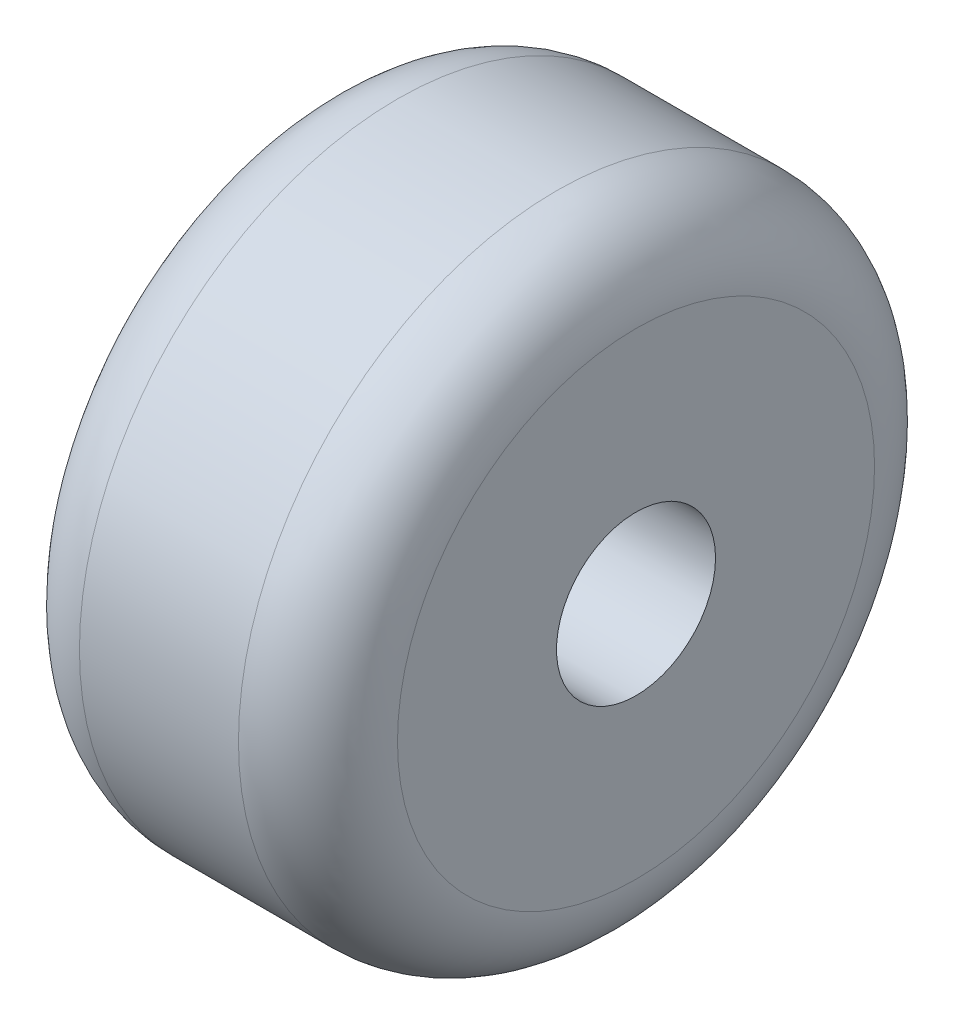
SolidWorks part; units mm, degrees
ref_plane "Front Plane" through (0, 0, 0) normal (0, 0, 1) x (1, 0, 0)
ref_plane "Top Plane" through (0, 0, 0) normal (0, 1, 0) x (1, 0, 0)
ref_plane "Right Plane" through (0, 0, 0) normal (1, 0, 0) x (0, 0, -1)
sketch "Sketch2" plane through (0, 0, 0) normal (1, 0, 0) x (0, 0, -1)
  circle A0 centre (0, 0) radius 25.4
  dimension "D1" = 50.8
extrude "Boss-Extrude1" add sketch "Sketch2" along normal blind 25.4
fillet "Fillet1" radius 6.35 2 edges at (0, 0, -25.4) (25.4, 0, -25.4)
sketch "Sketch3" plane through (25.4, 0, 0) normal (1, 0, 0) x (0, 0, -1)
  circle A0 centre (0, 0) radius 6.35
  dimension "D1" = 12.7
extrude "Cut-Extrude1" cut sketch "Sketch3" against normal blind 25.4
